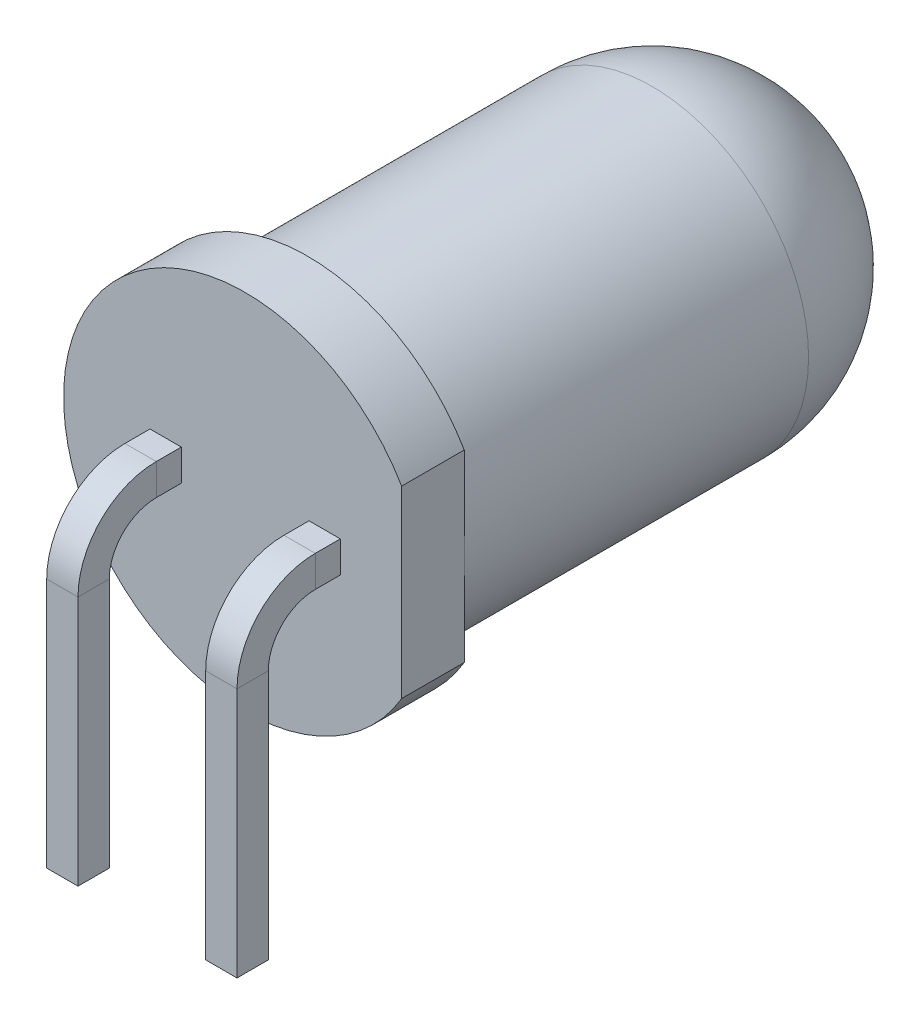
SolidWorks part; units mm, degrees
ref_plane "Front Plane" through (0, 0, 0) normal (0, 0, 1) x (1, 0, 0)
ref_plane "Top Plane" through (0, 0, 0) normal (0, 1, 0) x (1, 0, 0)
ref_plane "Right Plane" through (0, 0, 0) normal (1, 0, 0) x (0, 0, -1)
sketch "Sketch1" plane through (0, 0, 0) normal (0, 1, 0) x (1, 0, 0)
  line L0 (0, 0) -> (0, 9)
  line L1 (2.5, 6.5) -> (2.5, 1)
  line L2 (2.9, 0) -> (0, 0)
  line L3 (2.5, 1) -> (2.9, 1)
  line L4 (2.9, 1) -> (2.9, 0)
  arc A0 (0, 9) -> (2.5, 6.5) centre (0, 6.5) cw
  dimension "D1" = 2.5
  dimension "D2" = 2.9
  dimension "D3" = 1
  dimension "D4" = 9
revolve "Revolve1" add sketch "Sketch1" angle 360 about L0
sketch "Sketch2" plane through (0, 0, 0) normal (0, 0, 1) x (1, 0, 0)
  line L1 (2.9, 1.4697) -> (2.5, 1.4697)
  line L2 (2.9, 1.4697) -> (2.9, -1.4697)
  line L3 (2.9, -1.4697) -> (2.5, -1.4697)
  line L4 (2.5, 1.4697) -> (2.5, -1.4697)
  circle A0 centre (0, 0) radius 2.5 construction
  circle A1 centre (0, 0) radius 2.9 construction
extrude "Cut-Extrude1" cut sketch "Sketch2" against normal through all
sketch "Sketch3" plane through (0, 0, 0) normal (0, 0, 1) x (1, 0, 0)
  line L0 (0, 1.7562) -> (0, 0) construction
  line L1 (0, 0) -> (1.27, 0) construction
  line L2 (-1.02, 0.25) -> (-1.02, -0.25)
  line L3 (1.02, 0.25) -> (1.52, 0.25)
  line L4 (1.02, 0.25) -> (1.02, -0.25)
  line L5 (1.02, -0.25) -> (1.52, -0.25)
  line L6 (1.52, 0.25) -> (1.52, -0.25)
  line L7 (1.02, 0.25) -> (1.52, -0.25) construction
  line L8 (1.02, -0.25) -> (1.52, 0.25) construction
  line L9 (-1.02, -0.25) -> (-1.52, -0.25)
  line L10 (-1.52, 0.25) -> (-1.52, -0.25)
  line L11 (-1.02, 0.25) -> (-1.52, 0.25)
  dimension "D1" = 0.5
  dimension "D2" = 1.27
ref_plane "Plane1" through (1.27, 0, 0) normal (1, 0, 0) x (0, 0, -1)
sketch "Sketch4" plane through (1.27, 0, 0) normal (1, 0, 0) x (0, 0, -1)
  line L0 (0, 0) -> (-0.4, 0)
  line L1 (-1.4, -1) -> (-1.4, -5)
  arc A0 (-1.4, -1) -> (-0.4, 0) centre (-0.4, -1) cw
  point P7 (-0.7306, -0.0664)
  dimension "D3" = 1
  dimension "D1" = 0.4
  dimension "D2" = 5
sweep "Sweep1" add profiles "Sketch3" path "Sketch4"
